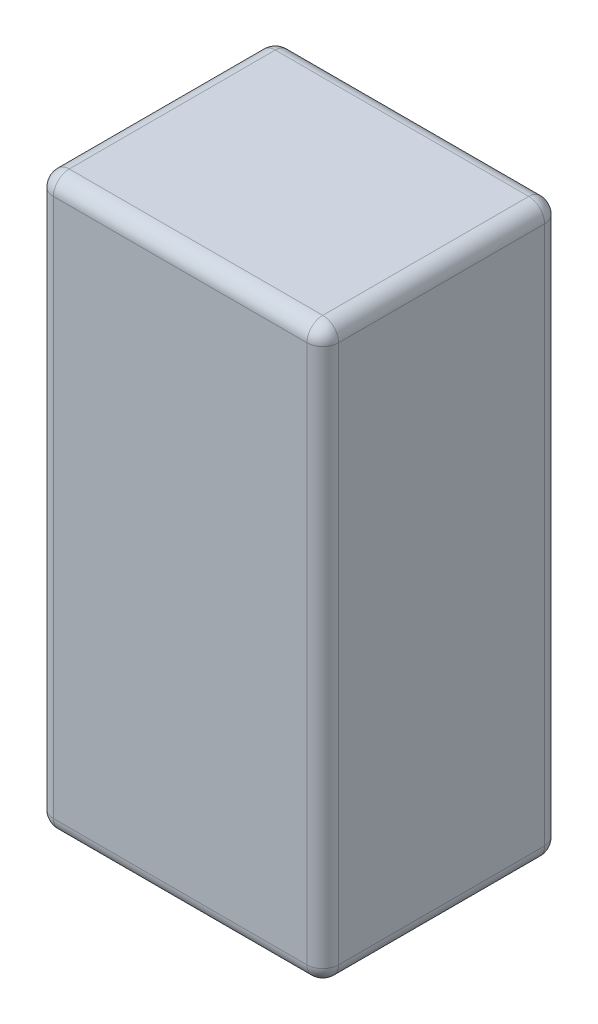
SolidWorks part; units mm, degrees
ref_plane "Alzado" through (0, 0, 0) normal (0, 0, 1) x (1, 0, 0)
ref_plane "Planta" through (0, 0, 0) normal (0, 1, 0) x (1, 0, 0)
ref_plane "Vista lateral" through (0, 0, 0) normal (1, 0, 0) x (0, 0, -1)
sketch "Croquis1" plane through (0, 0, 0) normal (0, 1, 0) x (1, 0, 0)
  line L1 (18, -15) -> (-18, -15)
  line L2 (18, -15) -> (18, 15)
  line L3 (18, 15) -> (-18, 15)
  line L4 (-18, -15) -> (-18, 15)
  line L5 (18, -15) -> (-18, 15) construction
  line L6 (18, 15) -> (-18, -15) construction
  point P0 (0, 0)
  dimension "D1" = 36
  dimension "D2" = 30
extrude "Saliente-Extruir1" add sketch "Croquis1" along normal blind 72
fillet "Redondeo1" radius 2 12 edges at (-18, 0, 0) (-18, 36, -15) (0, 0, -15) (18, 36, -15) (18, 0, 0) (-18, 36, 15) (18, 36, 15) (0, 0, 15) (0, 72, -15) (18, 72, 0) (0, 72, 15) (-18, 72, 0)
sketch "Croquis2" plane through (0, 0, 0) normal (0, -1, 0) x (1, 0, 0)
  line L0 (-16, -13) -> (16, -13) construction
  point P0 (-4, -13)
  point P1 (4, -13)
  dimension "D1" = 8
  dimension "D2" = 4
